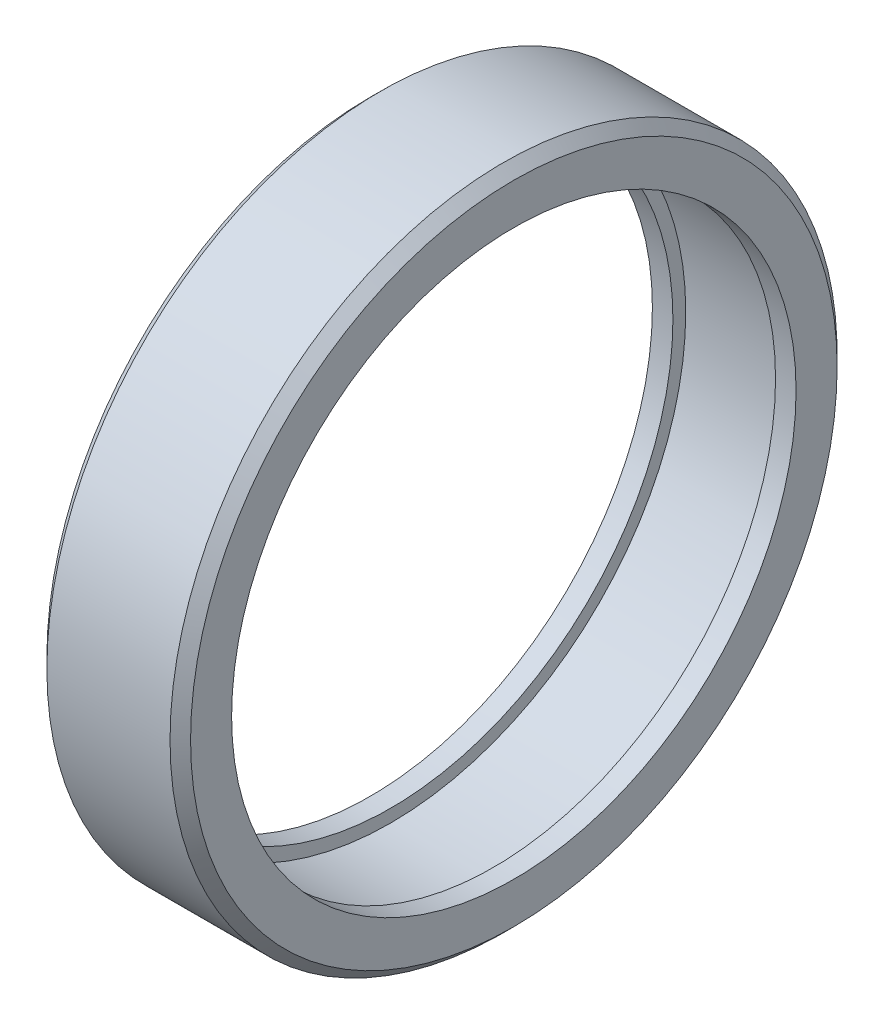
SolidWorks part; units mm, degrees
ref_plane "Front Plane" through (0, 0, 0) normal (0, 0, 1) x (1, 0, 0)
ref_plane "Top Plane" through (0, 0, 0) normal (0, 1, 0) x (1, 0, 0)
ref_plane "Right Plane" through (0, 0, 0) normal (1, 0, 0) x (0, 0, -1)
sketch "Sketch1" plane through (0, 0, 0) normal (0, 0, 1) x (1, 0, 0)
  line L0 (0, 39.5) -> (0, 42.5) construction
  line L1 (-10, 55) -> (-14, 55)
  line L3 (10, 55) -> (10, 57.5)
  line L4 (10, 57.5) -> (-10, 57.5)
  line L5 (-10, 55) -> (-10, 57.5)
  line L6 (0, 50) -> (-10, 57.5) construction
  line L7 (10, 57.5) -> (0, 50) construction
  line L8 (-14, 55) -> (-14, 65)
  line L9 (-14, 65) -> (14, 65)
  line L10 (14, 65) -> (14, 55)
  line L11 (14, 55) -> (10, 55)
  line L12 (0, 0) -> (57.162, 0) construction
  dimension "D4" = 4
  dimension "D5" = 10
  dimension "D6" = 28
  dimension "D7" = 10
  dimension "D13" = 2.5
revolve "Revolve1" add sketch "Sketch1" angle 360 about L12
chamfer "Chamfer1" distance 2 angle 45 2 edges at (14, 0, 65) (-14, 0, 65)
